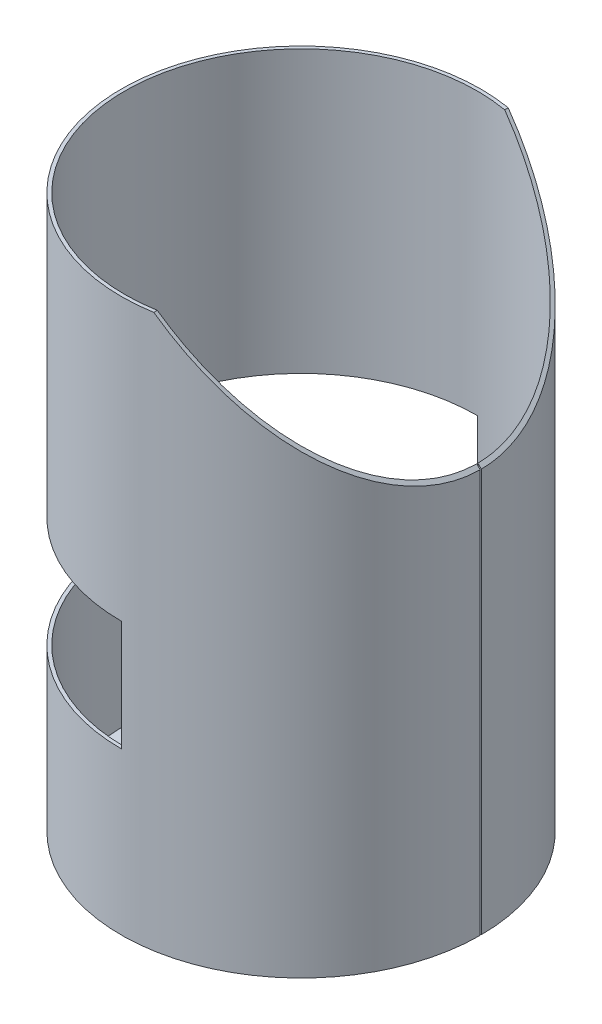
SolidWorks part; units mm, degrees
ref_plane "Plan de face" through (0, 0, 0) normal (0, 0, 1) x (1, 0, 0)
ref_plane "Plan de dessus" through (0, 0, 0) normal (0, 1, 0) x (1, 0, 0)
ref_plane "Plan de droite" through (0, 0, 0) normal (1, 0, 0) x (0, 0, -1)
sketch "Esquisse1" plane through (0, 0, 0) normal (0, 1, 0) x (1, 0, 0)
  circle A0 centre (0, 0) radius 156
  dimension "D1" = 312
extrude "Boss.-Extru.1" add sketch "Esquisse1" along normal blind 520
shell "Coque1" thickness 3
sketch "Esquisse2" plane through (0, 0, 0) normal (0, 0, 1) x (1, 0, 0)
  line L0 (0, 0) -> (0, 140) construction
  line L1 (0, 140) -> (-156.8219, 140)
  line L2 (0, 140) -> (0, 236)
  line L3 (0, 236) -> (-156, 236)
  line L4 (-156, 520) -> (-156, 0) construction
  line L5 (-156, 236) -> (-156.8219, 140)
  line L6 (-156, 0) -> (156, 0) construction
  line L7 (-156, 520) -> (-156, 480)
  line L8 (-156, 480) -> (26, 480)
  line L9 (26, 480) -> (156, 350)
  line L10 (156, 0) -> (156, 520) construction
  line L11 (156, 350) -> (156, 520)
  line L12 (156, 520) -> (-156, 520)
  dimension "D1" = 140
  dimension "D2" = 96
  dimension "D3" = 40
  dimension "D4" = 45
  dimension "D5" = 130
extrude "Enlèv. mat.-Extru.1" cut sketch "Esquisse2" against normal through all both and the other way through all
sketch "Esquisse3" plane through (0, 0, 0) normal (1, 0, 0) x (0, 0, -1)
  line L0 (-156, 0) -> (156, 0) construction
  line L1 (-0.5, 0) -> (0.5, 0)
  line L2 (-0.5, 0) -> (-0.5, 353.0008)
  line L3 (-0.5, 353.0008) -> (0.5, 353.0008)
  line L4 (0.5, 0) -> (0.5, 353.0008)
  ellipse E0 centre (0, 506) end of major axis (0, 353) minor radius 153 (-150.7747, 480) -> (150.7747, 480) ccw construction
  point P13 (0, 0)
  dimension "D1" = 1
extrude "Enlèv. mat.-Extru.2" cut sketch "Esquisse3" along normal through all
